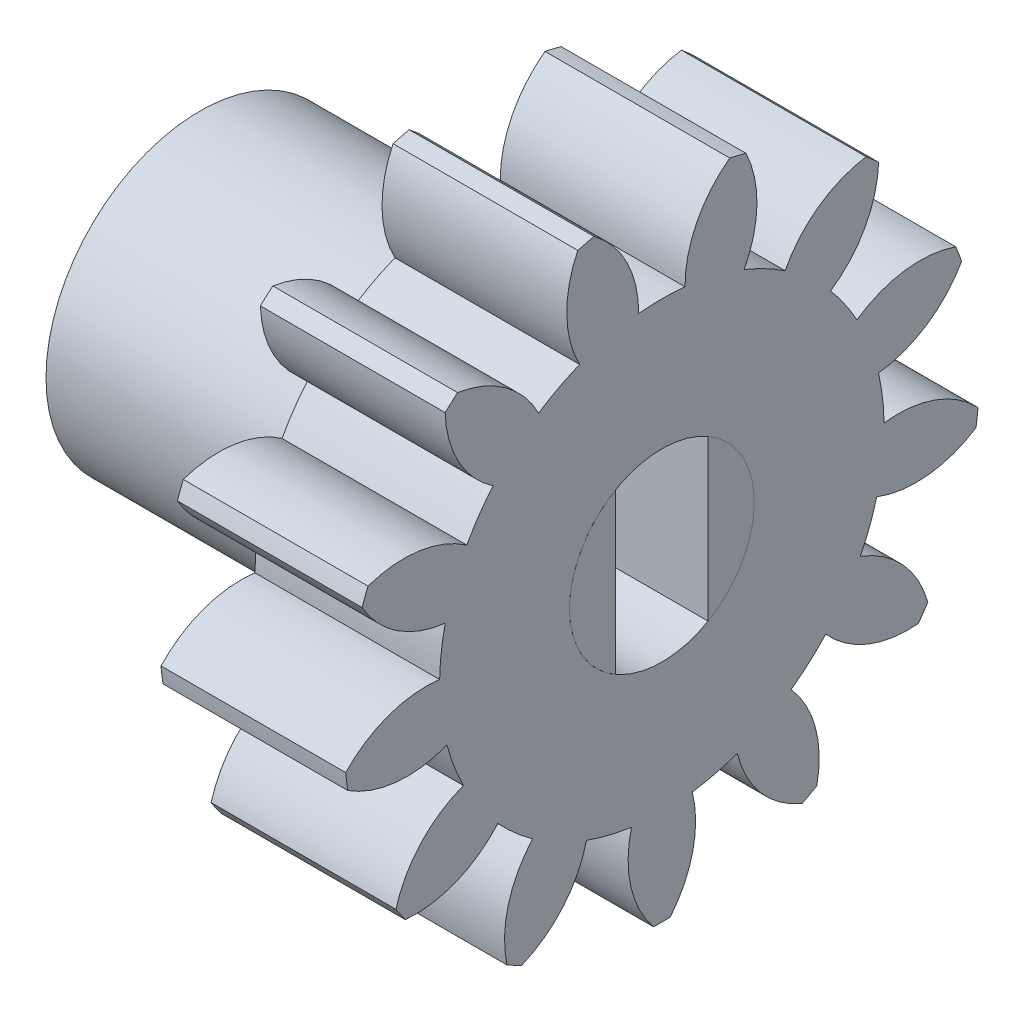
SolidWorks part; units mm, degrees
ref_plane "Plane1" through (0, 0, 0) normal (0, 0, 1) x (1, 0, 0)
ref_plane "Plane2" through (0, 0, 0) normal (0, 1, 0) x (1, 0, 0)
ref_plane "Plane3" through (0, 0, 0) normal (1, 0, 0) x (0, 0, -1)
sketch "HoldingSke" plane through (0, 0, 0) normal (0, 1, 0) x (1, 0, 0)
  line L0 (0, 0) -> (0.7086, -0.1636)
  line L1 (-15, 0) -> (100, 0) construction
  line L2 (0, 0) -> (-2.1039, 2.3779)
  line L3 (0, 0) -> (-11.863, 4.5341)
  line L4 (0, 0) -> (8.4147, 1.9427)
  line L5 (0, 0) -> (-14.0543, -5.2418)
  line L6 (0, 0) -> (-4.9738, -3.3558)
  line L7 (-2.1039, 2.3779) -> (1.1249, 17.0263)
  line L8 (-76.2, 54.61) -> (-75.2, 54.61)
  line L9 (-71.009, 38.7566) -> (-53.1078, 45.2721)
  line L10 (-76.2, 71.12) -> (104.1128, 71.12)
  line L11 (0, 0) -> (-6, 0)
  line L12 (-76.2, 101.6) -> (-76.151, 101.6)
  line L13 (24.9733, 27.94) -> (52.9518, 28.4284)
  line L14 (24.9733, 27.94) -> (24.9743, 27.94)
  line L15 (24.9733, 27.94) -> (100.4006, 29.5858)
  line L16 (-63.627, -1.375) -> (-12.827, -1.375)
  circle A0 centre (0, 0) radius 3
  circle A1 centre (0, 0) radius 5
  circle A2 centre (0, 0) radius 5
  circle A3 centre (0, 0) radius 3
  dimension "MHD" = 10
  dimension "Hub_dia" = 10
  dimension "Bore" = 6
  dimension "MBD" = 6
  dimension "Num_teeth" = 13
  dimension "Pitch" = 0.7273
  dimension "Overall_len" = 15
  dimension "Show_teeth" = 13
  dimension "Thickness" = 6
  dimension "OAL" = 15.0001
  dimension "T_dim" = 1
  dimension "Ap" = 20
  dimension "H" = 19.05
  dimension "Pitch_radius" = 180.3128
  dimension "Width" = 6
  dimension "Backlash" = 0.049
  dimension "Addendum_fac" = 1
  dimension "Dedendum_fac" = 1.25
  dimension "Clearance_fac" = 0.25
  dimension "Dedendum_add" = 0.001
  dimension "Module" = 1.375
sketch "BasProSke" plane through (0, 0, 0) normal (0, 1, 0) x (1, 0, 0)
  line L0 (-10, 0) -> (60, 0) construction
  line L1 (0, 0) -> (0, 10.3125)
  line L2 (0, 0) -> (6, 0)
  line L3 (6, 0) -> (6, 10.3125)
  line L4 (6, 10.3125) -> (0, 10.3125)
  dimension "Thickness" = 6
  dimension "Diameter" = 20.625
revolve "Base-Revolve" add sketch "BasProSke" angle 360 about L0
sketch "TooCutSke" plane through (0, 0, 0) normal (1, 0, 0) x (0, 0, -1)
  line L1 (0, 0) -> (0, 107) construction
  line L2 (0, 0) -> (-1.1629, 8.8615) construction
  line L3 (0, 0) -> (-4.2514, 17.2484) construction
  line L4 (-1.1629, 8.8615) -> (-2.1257, 8.6242) construction
  arc A0 (0.7523, 7.1784) -> (-0.7523, 7.1784) centre (0, 0) ccw
  arc A1 (2.2315, 10.0942) -> (-2.2315, 10.0942) centre (0, 0) ccw
  circle A2 centre (0, 0) radius 8.9375 construction
  circle A3 centre (0, 0) radius 8.3985 construction
  arc A4 (-0.7523, 7.1784) -> (-2.2315, 10.0942) centre (-4.3273, 7.1979) ccw
  arc A5 (2.2315, 10.0942) -> (0.7523, 7.1784) centre (4.3273, 7.1979) ccw
  dimension "Root_dia" = 14.4355
  dimension "Overcut_dia" = 20.6758
  dimension "Pitch_dia" = 17.875
  dimension "Base_dia" = 16.797
  dimension "Flank_rad" = 3.575
  dimension "Half_ang" = 13.846
  dimension "Half_CT" = 0.9915
extrude "ToothCut" cut sketch "TooCutSke" along normal through all
fillet "Breaks" [suppressed] radius 0.0275
fillet "RootFillets" [suppressed] radius 0.3448
pattern_circular "TeethCuts" count 13 every 27.692 about axis through (-10, 0, 0) along (1, 0, 0) of "ToothCut", "RootFillets", "Breaks"
sketch "HubNeaOneSke" plane through (0, 0, 0) normal (-1, 0, 0) x (0, 0, 1)
  circle A0 centre (0, 0) radius 5
  dimension "Diameter" = 10
extrude "HubNearOne" add sketch "HubNeaOneSke" along normal blind 9.0001
sketch "HubNeaBotSke" plane through (0, 0, 0) normal (-1, 0, 0) x (0, 0, 1)
  circle A0 centre (0, 0) radius 5
  dimension "Diameter" = 10
extrude "HubNearBoth" [suppressed] add sketch "HubNeaBotSke" along normal blind 4.5
ref_plane "FarPln" through (6, 0, 0) normal (1, 0, 0) x (0, 0, -1)
sketch "HubFarSke" plane through (6, 0, 0) normal (1, 0, 0) x (0, 0, -1)
  circle A0 centre (0, 0) radius 5
  dimension "Diameter" = 10
extrude "HubFar" [suppressed] add sketch "HubFarSke" along normal blind 4.5
sketch "BorSke" plane through (0, 0, 0) normal (1, 0, 0) x (0, 0, -1)
  circle A0 centre (0, 0) radius 3
  dimension "Diameter" = 6
extrude "Bore" cut sketch "BorSke" along normal mid plane 30.0001
sketch "KeySke" plane through (0, 0, 0) normal (1, 0, 0) x (0, 0, -1)
  line L0 (-1, 0) -> (-1, 4)
  line L1 (-1, 4) -> (1, 4)
  line L2 (1, 4) -> (1, 0)
  line L3 (0, 0) -> (0, 34) construction
  line L4 (-1, 0) -> (1, 0)
  dimension "Offset" = 4
  dimension "Width" = 2
extrude "Keyway" [suppressed] cut sketch "KeySke" along normal mid plane 30.0001
pattern_circular "Keyway2" [suppressed] count 2 every 90 about axis through (-10, 0, 0) along (1, 0, 0)
sketch "Esboço1" plane through (6, 0, 0) normal (1, 0, 0) x (0, 0, -1)
  line L2 (-1.5, -2.5981) -> (-1.5, 2.5981)
  line L4 (1.5, -2.5981) -> (1.5, 2.5981)
  line L6 (-1.1848, 2.7561) -> (0, 0) construction
  arc A0 (-1.5, 2.5981) -> (-1.5, -2.5981) centre (0, 0) ccw
  arc A1 (1.5, -2.5981) -> (1.5, 2.5981) centre (0, 0) ccw
extrude "Ressalto-extrusão1" add sketch "Esboço1" against normal up to surface (15.0001 mm away) separate body up to face at (-9.0001, 0, 3)
equation "' \"Module@HoldingSke\" = 6.35"
equation "' \"Num_teeth@HoldingSke\" = 12"
equation "' \"Ap@HoldingSke\" =  20"
equation "' \"Ap@HoldingSke\" = 20"
equation "' \"Width@HoldingSke\" = 0.5 * 25.4"
equation "' \"Hub_dia@HoldingSke\"= 1 * 25.4"
equation "' \"Hub_dia@HoldingSke\" = 1 * 25.4"
equation "' \"Overall_len@HoldingSke\" = 1.0 * 25.4"
equation "' \"Bore@HoldingSke\" = 0.75 * 25.4"
equation "' \"T_dim@HoldingSke\" = 0.1 * 25.4"
equation "' \"Width@KeySke\" = 0.25 * 25.4"
equation "' \"Show_teeth@HoldingSke\" = 13"
equation "' \"Backlash@HoldingSke\" = 0.009 * 25.4"
equation "' \"Addendum_fac@HoldingSke\" = 1.0"
equation "' \"Dedendum_fac@HoldingSke\" = 1.25"
equation "' \"Dedendum_add@HoldingSke\" = 0.00005 * 25.4"
equation "' \"Clearance_fac@HoldingSke\" = 0.25"
equation "\"Pitch@HoldingSke\" = 1 / \"Module@HoldingSke\""
equation "\"Overcut_dia@TooCutSke\" = (\"Num_teeth@HoldingSke\" + 2 * \"Addendum_fac@HoldingSke\") / \"Pitch@HoldingSke\" + 0.002 * 25.4"
equation "\"Pitch_dia@TooCutSke\" = \"Num_teeth@HoldingSke\" / \"Pitch@HoldingSke\""
equation "\"Base_dia@TooCutSke\" = \"Num_teeth@HoldingSke\" / \"Pitch@HoldingSke\" * cos((\"Ap@HoldingSke\"  * 3.14159265 / 180))"
equation "\"Root_dia@TooCutSke\" = (\"Num_teeth@HoldingSke\" + 2) / \"Pitch@HoldingSke\" - 2 * (\"Addendum_fac@HoldingSke\" + \"Dedendum_fac@HoldingSke\") / \"Pitch@HoldingSke\" - \"Dedendum_add@HoldingSke\" * 2"
equation "\"Half_ang@TooCutSke\" = 180 / \"Num_teeth@HoldingSke\""
equation "\"Half_CT@TooCutSke\" = \"Num_teeth@HoldingSke\" / \"Pitch@HoldingSke\" * sin((3.14159265 / 2 / \"Num_teeth@HoldingSke\")) / 2 - 7 * \"Backlash@HoldingSke\" / 4"
equation "\"Flank_rad@TooCutSke\" = \"Num_teeth@HoldingSke\" / \"Pitch@HoldingSke\" / 5"
equation "\"Radius@RootFillets\" = \"Clearance_fac@HoldingSke\" / \"Pitch@HoldingSke\" + \"Dedendum_add@HoldingSke\""
equation "\"Break_rad@Breaks\" = 0.02 / \"Pitch@HoldingSke\""
equation "\"Thickness@HoldingSke\" = \"Width@HoldingSke\""
equation "\"OAL@HoldingSke\" = \"Thickness@HoldingSke\""
equation "\"MHD@HoldingSke\" = (\"Num_teeth@HoldingSke\" + 2) / \"Pitch@HoldingSke\" - 2 * (\"Addendum_fac@HoldingSke\" + \"Dedendum_fac@HoldingSke\")  / \"Pitch@HoldingSke\" - \"Dedendum_add@HoldingSke\" * 2"
equation "\"MBD@HoldingSke\" = (\"Num_teeth@HoldingSke\" + 2) / \"Pitch@HoldingSke\" - 2 * (\"Addendum_fac@HoldingSke\" + \"Dedendum_fac@HoldingSke\")  / \"Pitch@HoldingSke\" - \"Dedendum_add@HoldingSke\" * 2 - 0.002 * 25.4"
equation "\"MHD@HoldingSke\" = ((sgn( \"MHD@HoldingSke\" - \"Hub_dia@HoldingSke\" )-1)*( \"MHD@HoldingSke\" - \"Hub_dia@HoldingSke\" ))/-2+ \"Hub_dia@HoldingSke\""
equation "\"MBD@HoldingSke\" = ((sgn( \"MBD@HoldingSke\" - \"Bore@HoldingSke\" )-1)*( \"MBD@HoldingSke\" - \"Bore@HoldingSke\" ))/-2+ \"Bore@HoldingSke\""
equation "\"OAL@HoldingSke\" = ((sgn( \"OAL@HoldingSke\" - \"Overall_len@HoldingSke\" )+1)*( \"OAL@HoldingSke\" - \"Overall_len@HoldingSke\" ))/2 + \"Overall_len@HoldingSke\" + 0.000002 * 25.4"
equation "\"Num_teeth@TeethCuts\" = int( \"Show_teeth@HoldingSke\" ) + 1"
equation "\"Num_teeth@TeethCuts\" = ((sgn( \"Num_teeth@TeethCuts\" - \"Num_teeth@HoldingSke\" )-1)*( \"Num_teeth@TeethCuts\" - \"Num_teeth@HoldingSke\" ))/-2+ \"Num_teeth@HoldingSke\""
equation "\"Num_teeth@TeethCuts\" = ((sgn( \"Num_teeth@TeethCuts\" - 2.0)+1)*( \"Num_teeth@TeethCuts\" - 2.0))/2 +2.0"
equation "\"Angle@TeethCuts\" = 360.0 / \"Num_teeth@HoldingSke\""
equation "\"Diameter@BasProSke\" = (\"Num_teeth@HoldingSke\" + 2 * \"Addendum_fac@HoldingSke\") / \"Pitch@HoldingSke\""
equation "\"Thickness@BasProSke\"  = \"Thickness@HoldingSke\""
equation "' \"Fillet_rad@BasProSke\" =  \"Thickness@HoldingSke\" * 0.05"
equation "' \"Fillet_rad@BasProSke\" = \"Thickness@HoldingSke\" * 0.05"
equation "\"MHD@HoldingSke\" = ((sgn( \"MHD@HoldingSke\" - \"Root_dia@TooCutSke\" )-1)*( \"MHD@HoldingSke\" - \"Root_dia@TooCutSke\" ))/-2+ \"Root_dia@TooCutSke\""
equation "\"Diameter@HubNeaOneSke\" = \"MHD@HoldingSke\""
equation "\"Length@HubNearOne\" = \"OAL@HoldingSke\" - \"Thickness@BasProSke\""
equation "\"Diameter@HubNeaBotSke\" = \"MHD@HoldingSke\""
equation "\"Length@HubNearBoth\" = ( \"OAL@HoldingSke\" - \"Thickness@BasProSke\" ) / 2.0"
equation "\"Thickness@FarPln\" = \"Thickness@BasProSke\""
equation "\"Diameter@HubFarSke\" = \"MHD@HoldingSke\""
equation "\"Length@HubFar\" = ( \"OAL@HoldingSke\" - \"Thickness@BasProSke\" ) / 2.0"
equation "\"Diameter@BorSke\" = \"MBD@HoldingSke\""
equation "\"D1@Bore\" = \"OAL@HoldingSke\" * 2.0"
equation "\"D1@Keyway\" = \"OAL@HoldingSke\" * 2.0"
equation "\"Offset@KeySke\" = \"T_dim@HoldingSke\" + \"MBD@HoldingSke\" / 2.0"
